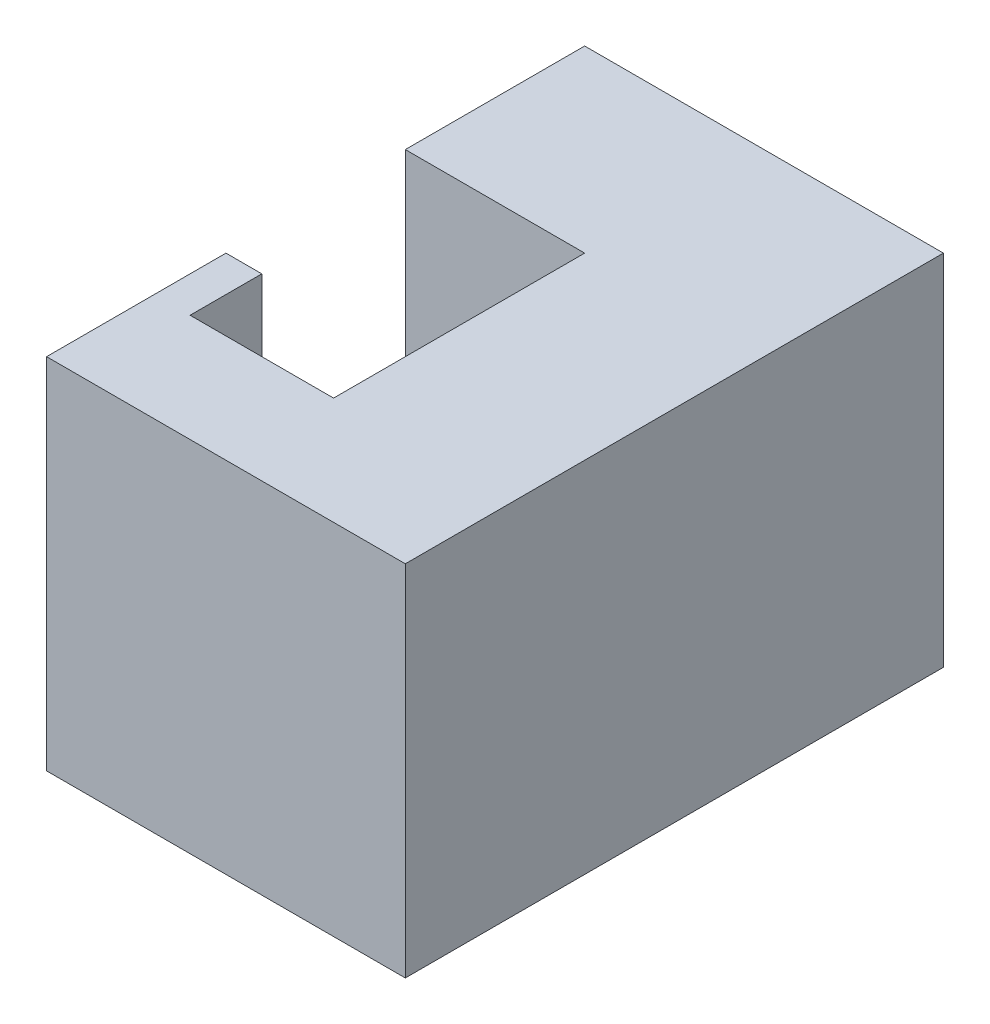
SolidWorks part; units mm, degrees
ref_plane "Front" through (0, 0, 0) normal (0, 0, 1) x (1, 0, 0)
ref_plane "Top" through (0, 0, 0) normal (0, 1, 0) x (1, 0, 0)
ref_plane "Right" through (0, 0, 0) normal (1, 0, 0) x (0, 0, -1)
sketch "Sketch2" plane through (0, 0, 0) normal (0, 1, 0) x (1, 0, 0)
  line L1 (-2.5, -3.75) -> (2.5, -3.75)
  line L2 (-2.5, -3.75) -> (-2.5, 3.75)
  line L3 (-2.5, 3.75) -> (2.5, 3.75)
  line L4 (2.5, -3.75) -> (2.5, 3.75)
  line L5 (-2.5, -3.75) -> (2.5, 3.75) construction
  line L6 (-2.5, 3.75) -> (2.5, -3.75) construction
  point P0 (0, 0)
  dimension "D1" = 5
  dimension "D2" = 7.5
extrude "Boss-Extrude1" add sketch "Sketch2" along normal blind 5
sketch "Sketch3" plane through (0, 0, 0) normal (0, -1, 0) x (1, 0, 0)
  line L0 (-2.5, -1.25) -> (0, -1.25)
  line L1 (-2.5, -3.75) -> (-2.5, 3.75) construction
  line L2 (0, -1.25) -> (0, 2.25)
  line L3 (0, 2.25) -> (-2, 2.25)
  line L4 (-2, 2.25) -> (-2, 1.25)
  line L5 (-2, 1.25) -> (-2.5, 1.25)
  line L8 (2.5, -3.75) -> (-2.5, -3.75) construction
  point P4 (0, 0)
  dimension "D1" = 2.5
  dimension "D2" = 2.5
  dimension "D3" = 3.5
  dimension "D4" = 0.5
  dimension "D5" = 2.5
extrude "Cut-Extrude1" cut sketch "Sketch3" against normal blind 5 and the other way through all
